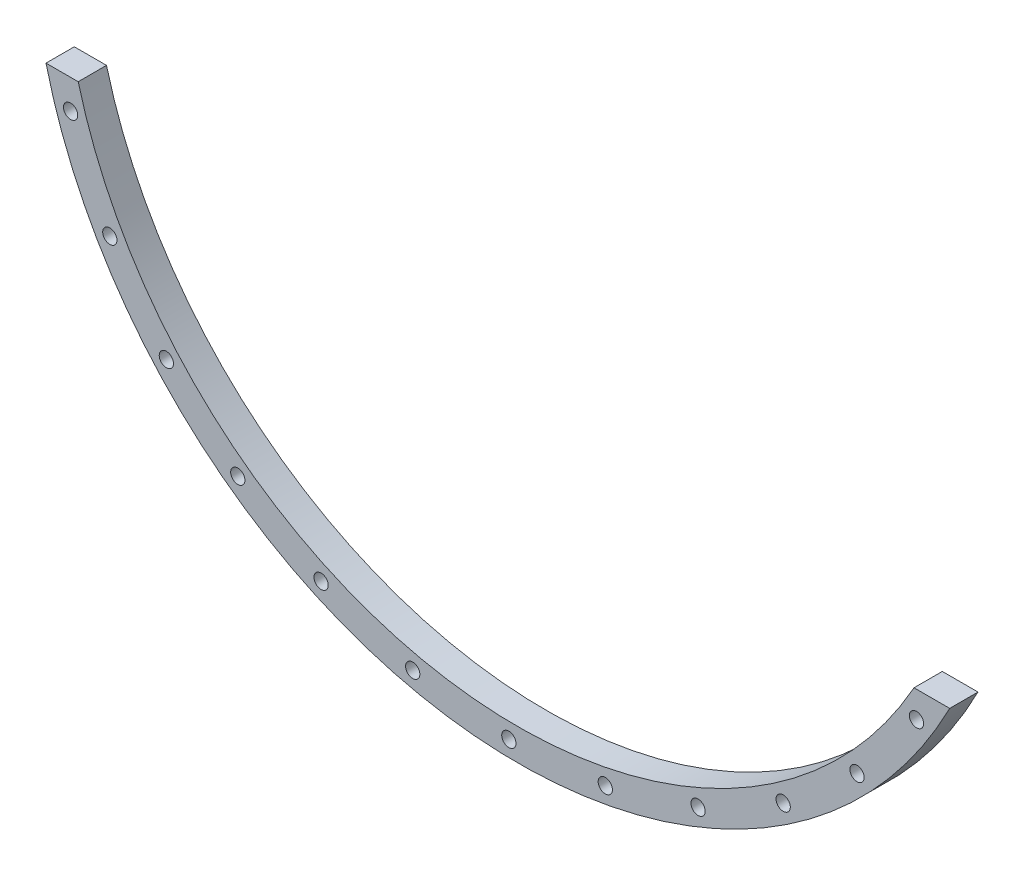
SolidWorks part; units mm, degrees
material "PE High Density"
ref_plane "Front Plane" through (0, 0, 0) normal (0, 0, 1) x (1, 0, 0)
ref_plane "Top Plane" through (0, 0, 0) normal (0, 1, 0) x (1, 0, 0)
ref_plane "Right Plane" through (0, 0, 0) normal (1, 0, 0) x (0, 0, -1)
sketch "Sketch1" plane through (0, 0, 0) normal (0, 0, 1) x (1, 0, 0)
  line L0 (88.9044, -50) -> (96.9118, -50) construction
  line L1 (-105.8537, -26) -> (-98.6306, -26) construction
  line L2 (88.9044, -50) -> (96.9118, -50)
  line L3 (-105.8537, -26) -> (-98.6306, -26)
  circle A0 centre (0, 0) radius 109 construction
  circle A1 centre (0, 0) radius 102 construction
  circle A2 centre (0, 0) radius 109 construction
  circle A3 centre (0, 0) radius 102 construction
  arc A4 (-98.6306, -26) -> (88.9044, -50) centre (0, 0) ccw
  arc A6 (-105.8537, -26) -> (96.9118, -50) centre (0.0181, -0.0739) ccw
extrude "Boss-Extrude1" add sketch "Sketch1" along normal mid plane 6.35
sketch "Sketch4" plane through (0, 0, 3.175) normal (0, 0, 1) x (1, 0, 0)
  circle A1 centre (-103.1946, -21.9347) radius 1.6
  circle A2 centre (-103.1946, -21.9347) radius 1.6
  circle A3 centre (-105.4075, -4.4179) radius 1.6
  circle A4 centre (-105.4075, -4.4179) radius 1.6
  circle A5 centre (-104.6681, -13.2227) radius 1.6
  circle A6 centre (-104.6681, -13.2227) radius 1.6
  circle A7 centre (-100.3365, 32.6013) radius 1.6
  circle A8 centre (-100.3365, 32.6013) radius 1.6
  circle A9 centre (104.2954, 15.8973) radius 1.6
  circle A10 centre (104.2954, 15.8973) radius 1.6
  circle A11 centre (100.709, 31.4316) radius 1.6
  circle A12 centre (100.709, 31.4316) radius 1.6
  circle A13 centre (94.8228, 46.2482) radius 1.6
  circle A14 centre (94.8228, 46.2482) radius 1.6
  circle A15 centre (-103.1946, 21.9347) radius 1.6
  circle A16 centre (-103.1946, 21.9347) radius 1.6
  circle A17 centre (-104.6681, 13.2227) radius 1.6
  circle A18 centre (-104.6681, 13.2227) radius 1.6
  circle A19 centre (-105.4075, 4.4179) radius 1.6
  circle A20 centre (-105.4075, 4.4179) radius 1.6
  circle A21 centre (89.4691, -55.9065) radius 1.6
  circle A22 centre (89.4691, -55.9065) radius 1.6
  circle A23 centre (-44.1306, 95.8266) radius 1.6
  circle A24 centre (-44.1306, 95.8266) radius 1.6
  circle A25 centre (-62.8211, 84.7571) radius 1.6
  circle A26 centre (-62.8211, 84.7571) radius 1.6
  circle A27 centre (-78.8482, 70.0943) radius 1.6
  circle A28 centre (-78.8482, 70.0943) radius 1.6
  circle A29 centre (-91.5326, 52.4598) radius 1.6
  circle A30 centre (-91.5326, 52.4598) radius 1.6
  circle A31 centre (94.8228, -46.2482) radius 1.6
  circle A32 centre (94.8228, -46.2482) radius 1.6
  circle A33 centre (100.709, -31.4316) radius 1.6
  circle A34 centre (100.709, -31.4316) radius 1.6
  circle A35 centre (104.2954, -15.8973) radius 1.6
  circle A36 centre (104.2954, -15.8973) radius 1.6
  circle A37 centre (105.5, 0) radius 1.6
  circle A38 centre (105.5, 0) radius 1.6
  circle A39 centre (76.1225, -73.0453) radius 1.6
  circle A40 centre (76.1225, -73.0453) radius 1.6
  circle A41 centre (89.4691, 55.9065) radius 1.6
  circle A42 centre (89.4691, 55.9065) radius 1.6
  circle A43 centre (76.1225, 73.0453) radius 1.6
  circle A44 centre (76.1225, 73.0453) radius 1.6
  circle A45 centre (59.5488, 87.0873) radius 1.6
  circle A46 centre (59.5488, 87.0873) radius 1.6
  circle A47 centre (40.4504, 97.4372) radius 1.6
  circle A48 centre (40.4504, 97.4372) radius 1.6
  circle A49 centre (19.6372, 103.6563) radius 1.6
  circle A50 centre (19.6372, 103.6563) radius 1.6
  circle A51 centre (-2.0086, 105.4809) radius 1.6
  circle A52 centre (-2.0086, 105.4809) radius 1.6
  circle A53 centre (-23.5692, 102.8336) radius 1.6
  circle A54 centre (-23.5692, 102.8336) radius 1.6
  circle A55 centre (-91.5326, -52.4598) radius 1.6
  circle A56 centre (-91.5326, -52.4598) radius 1.6
  circle A57 centre (-62.8211, -84.7571) radius 1.6
  circle A58 centre (-62.8211, -84.7571) radius 1.6
  circle A59 centre (-44.1306, -95.8266) radius 1.6
  circle A60 centre (-44.1306, -95.8266) radius 1.6
  circle A61 centre (-23.5692, -102.8336) radius 1.6
  circle A62 centre (-23.5692, -102.8336) radius 1.6
  circle A63 centre (-2.0086, -105.4809) radius 1.6
  circle A64 centre (-2.0086, -105.4809) radius 1.6
  circle A65 centre (19.6372, -103.6563) radius 1.6
  circle A66 centre (19.6372, -103.6563) radius 1.6
  circle A67 centre (40.4504, -97.4372) radius 1.6
  circle A68 centre (40.4504, -97.4372) radius 1.6
  circle A69 centre (59.5488, -87.0873) radius 1.6
  circle A70 centre (59.5488, -87.0873) radius 1.6
  circle A71 centre (-78.8482, -70.0943) radius 1.6
  circle A72 centre (-78.8482, -70.0943) radius 1.6
  circle A73 centre (-100.3365, -32.6013) radius 1.6
  circle A74 centre (-100.3365, -32.6013) radius 1.6
  dimension "D1" = 0
  dimension "D2" = 0
  dimension "D3" = 0
  dimension "D4" = 0
  dimension "D5" = 0
  dimension "D6" = 0
  dimension "D7" = 0
  dimension "D8" = 0
  dimension "D9" = 0
  dimension "D10" = 0
  dimension "D11" = 0
  dimension "D12" = 0
  dimension "D13" = 0
  dimension "D14" = 0
  dimension "D15" = 0
  dimension "D16" = 0
  dimension "D17" = 0
  dimension "D18" = 0
  dimension "D19" = 0
  dimension "D20" = 0
  dimension "D21" = 0
  dimension "D22" = 0
  dimension "D23" = 0
  dimension "D24" = 0
  dimension "D25" = 0
  dimension "D26" = 0
  dimension "D27" = 0
  dimension "D28" = 0
  dimension "D29" = 0
  dimension "D30" = 0
  dimension "D31" = 0
  dimension "D32" = 0
  dimension "D33" = 0
  dimension "D34" = 0
  dimension "D35" = 0
  dimension "D36" = 0
  dimension "D37" = 0
extrude "Cut-Extrude3" cut sketch "Sketch4" against normal through all
